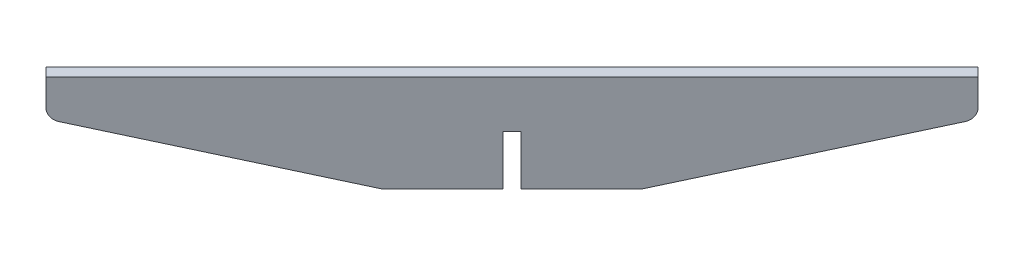
SolidWorks part; units mm, degrees
ref_plane "Front Plane" through (0, 0, 0) normal (0, 0, 1) x (1, 0, 0)
ref_plane "Top Plane" through (0, 0, 0) normal (0, 1, 0) x (1, 0, 0)
ref_plane "Right Plane" through (0, 0, 0) normal (1, 0, 0) x (0, 0, -1)
sketch "Sketch1" plane through (0, 0, 0) normal (0, 1, 0) x (1, 0, 0)
  line L0 (-195, -158.5534) -> (-158.5534, -195) construction
  line L1 (-195, 195) -> (195, 195) construction
  line L2 (-195, 195) -> (-195, -195) construction
  line L3 (-195, -195) -> (195, -195) construction
  line L4 (195, 195) -> (195, -195) construction
  line L5 (-195, 195) -> (195, -195) construction
  line L6 (-195, -195) -> (195, 195) construction
  line L7 (-195, -512.1068) -> (-512.1068, -195) construction
  line L8 (-195, -865.6602) -> (-865.6602, -195) construction
  line L9 (-865.6602, 195) -> (-195, 865.6602) construction
  line L10 (-512.1068, 195) -> (-195, 512.1068) construction
  line L11 (-158.5534, 195) -> (-195, 158.5534) construction
  line L12 (195, 865.6602) -> (865.6602, 195) construction
  line L13 (195, 512.1068) -> (512.1068, 195) construction
  line L14 (195, 158.5534) -> (158.5534, 195) construction
  line L15 (865.6602, -195) -> (195, -865.6602) construction
  line L16 (512.1068, -195) -> (195, -512.1068) construction
  line L17 (158.5534, -195) -> (195, -158.5534) construction
  line L18 (-195, -187.9289) -> (-187.9289, -195)
  line L19 (-195, -187.9289) -> (187.9289, 195)
  line L20 (-187.9289, -195) -> (195, 187.9289)
  line L21 (187.9289, 195) -> (195, 187.9289)
  line L22 (-195, 151.4823) -> (-202.0711, 158.5534) construction
  line L23 (-195, 151.4823) -> (-158.5534, 187.9289) construction
  line L24 (-202.0711, 158.5534) -> (-165.6245, 195) construction
  line L25 (-158.5534, 187.9289) -> (-165.6245, 195) construction
  line L26 (-195, 516.3494) -> (-190.7574, 512.1068) construction
  line L27 (-195, 516.3494) -> (-516.3494, 195) construction
  line L28 (-190.7574, 512.1068) -> (-512.1068, 190.7574) construction
  line L29 (-516.3494, 195) -> (-512.1068, 190.7574) construction
  line L32 (-195, 869.9028) -> (-190.7574, 865.6602) construction
  line L33 (-195, 869.9028) -> (-869.9028, 195) construction
  line L34 (-190.7574, 865.6602) -> (-865.6602, 190.7574) construction
  line L35 (-869.9028, 195) -> (-865.6602, 190.7574) construction
  point P0 (0, 0)
  point P12 (-191.4645, -191.4645)
  point P33 (0, 0)
  point P37 (-198.5355, 155.0179)
  point P40 (-162.0889, 191.4645)
  point P43 (-192.8787, 514.2281)
  point P44 (-192.8787, 867.7815)
  point P45 (-867.7815, 192.8787)
  point P46 (-514.2281, 192.8787)
  dimension "D1" = 390
  dimension "D2" = 250
  dimension "D3" = 250
  dimension "D4" = 250
  dimension "D6" = 250
  dimension "D7" = 250
  dimension "D8" = 10
  dimension "D9" = 10
  dimension "D10" = 6
  dimension "D11" = 6
  dimension "D5" = 4
extrude "Boss-Extrude1" add sketch "Sketch1" along normal mid plane 30
ref_plane "Plane1" through (0, 0, 0) normal (0.7071, 0, 0.7071) x (0.7071, 0, -0.7071)
ref_plane "Plane2" through (0, 0, 0) normal (-0.7071, 0, 0.7071) x (0.7071, 0, 0.7071)
sketch "Sketch2" plane through (0, 0, 0) normal (0.7071, 0, 0.7071) x (0.7071, 0, -0.7071)
  line L0 (0, 149.1941) -> (0, -149.1941) construction
  line L1 (-3.1, 0) -> (3.1, 0)
  line L2 (-3.1, 0) -> (-3.1, 50)
  line L3 (-3.1, 50) -> (3.1, 50)
  line L4 (3.1, 0) -> (3.1, 50)
  line L5 (-3.1, 0) -> (3.1, 50) construction
  line L6 (-3.1, 50) -> (3.1, 0) construction
  line L7 (-253.1, 0) -> (-246.9, 0)
  line L8 (-253.1, 0) -> (-253.1, 50)
  line L9 (-253.1, 50) -> (-246.9, 50)
  line L10 (-246.9, 0) -> (-246.9, 50)
  line L11 (-253.1, 0) -> (-246.9, 50) construction
  line L12 (-253.1, 50) -> (-246.9, 0) construction
  line L13 (-503.1, 0) -> (-496.9, 0)
  line L14 (-503.1, 0) -> (-503.1, 50)
  line L15 (-503.1, 50) -> (-496.9, 50)
  line L16 (-496.9, 0) -> (-496.9, 50)
  line L17 (-503.1, 0) -> (-496.9, 50) construction
  line L18 (-503.1, 50) -> (-496.9, 0) construction
  line L19 (-753.1, 0) -> (-746.9, 0)
  line L20 (-753.1, 0) -> (-753.1, 50)
  line L21 (-753.1, 50) -> (-746.9, 50)
  line L22 (-746.9, 0) -> (-746.9, 50)
  line L23 (-753.1, 0) -> (-746.9, 50) construction
  line L24 (-753.1, 50) -> (-746.9, 0) construction
  line L25 (699.6, 0) -> (-699.6, 0) construction
  line L27 (753.1, 50) -> (746.9, 0) construction
  line L28 (753.1, 0) -> (746.9, 50) construction
  line L29 (503.1, 50) -> (496.9, 0) construction
  line L30 (503.1, 0) -> (496.9, 50) construction
  line L31 (253.1, 50) -> (246.9, 0) construction
  line L32 (253.1, 0) -> (246.9, 50) construction
  line L33 (746.9, 0) -> (746.9, 50)
  line L34 (753.1, 50) -> (746.9, 50)
  line L35 (753.1, 0) -> (753.1, 50)
  line L36 (753.1, 0) -> (746.9, 0)
  line L37 (496.9, 0) -> (496.9, 50)
  line L38 (503.1, 50) -> (496.9, 50)
  line L39 (503.1, 0) -> (503.1, 50)
  line L40 (503.1, 0) -> (496.9, 0)
  line L41 (246.9, 0) -> (246.9, 50)
  line L42 (253.1, 50) -> (246.9, 50)
  line L43 (253.1, 0) -> (253.1, 50)
  line L44 (253.1, 0) -> (246.9, 0)
  point P0 (0, 25)
  point P5 (-250, 25)
  point P10 (-500, 25)
  point P15 (-750, 25)
  point P28 (-250, 0)
  point P30 (-500, 0)
  point P32 (-750, 0)
  point P46 (750, 25)
  point P47 (500, 25)
  point P48 (250, 25)
  dimension "D1" = 6.2
  dimension "D2" = 50
extrude "Cut-Extrude1" [suppressed] cut sketch "Sketch2" against normal through all both and the other way through all
sketch "Sketch3" plane through (0, 0, 0) normal (0.7071, 0, 0.7071) x (0.7071, 0, -0.7071)
  line L0 (270.7716, -15) -> (75, -65)
  line L1 (75, -65) -> (-75, -65)
  line L2 (-75, -65) -> (-270.7716, -15)
  line L3 (-270.7716, -15) -> (270.7716, -15)
  line L4 (0, 149.1941) -> (0, -149.1941) construction
  line L5 (270.7716, -15) -> (-270.7716, -15) construction
  point P2 (0, -15)
  point P9 (0, -65)
  dimension "D1" = 50
  dimension "D2" = 150
extrude "Boss-Extrude2" add sketch "Sketch3" along normal mid plane 10
sketch "Sketch4" plane through (0, 0, 0) normal (0.7071, 0, 0.7071) x (0.7071, 0, -0.7071)
  line L0 (0, 149.1941) -> (0, -149.1941) construction
  line L6 (-5.1, -106) -> (5.1, -106)
  line L8 (-75, -65) -> (75, -65) construction
  line L9 (-5.1, -106) -> (-5.1, -24)
  line L10 (-5.1, -24) -> (5.1, -24)
  line L11 (5.1, -106) -> (5.1, -24)
  line L12 (-5.1, -106) -> (5.1, -24) construction
  line L13 (-5.1, -24) -> (5.1, -106) construction
  point P0 (0, -65)
  point P1 (0, -65)
  dimension "D1" = 82
  dimension "D2" = 10.2
extrude "Cut-Extrude2" cut sketch "Sketch4" against normal through all both and the other way through all
ref_plane "Plane3" through (-3.5355, 0, -3.5355) normal (-0.7071, 0, -0.7071) x (-0.7071, 0, 0.7071)
ref_plane "Plane4" [suppressed] through (0, 0, 0) normal (-0.7071, 0, 0.7071) x (0.7071, 0, 0.7071)
ref_plane "Plane5" through (0, 0, 0) normal (-0.7071, 0, -0.7071) x (-0.7071, 0, 0.7071)
ref_plane "Plane6" through (0, 0, 0) normal (0.7071, 0, -0.7071) x (-0.7071, 0, -0.7071)
fillet "Fillet1" radius 10 1 edges at (191.4645, -15, -191.4645)
fillet "Fillet2" radius 10 1 edges at (-191.4645, -15, 191.4645)
